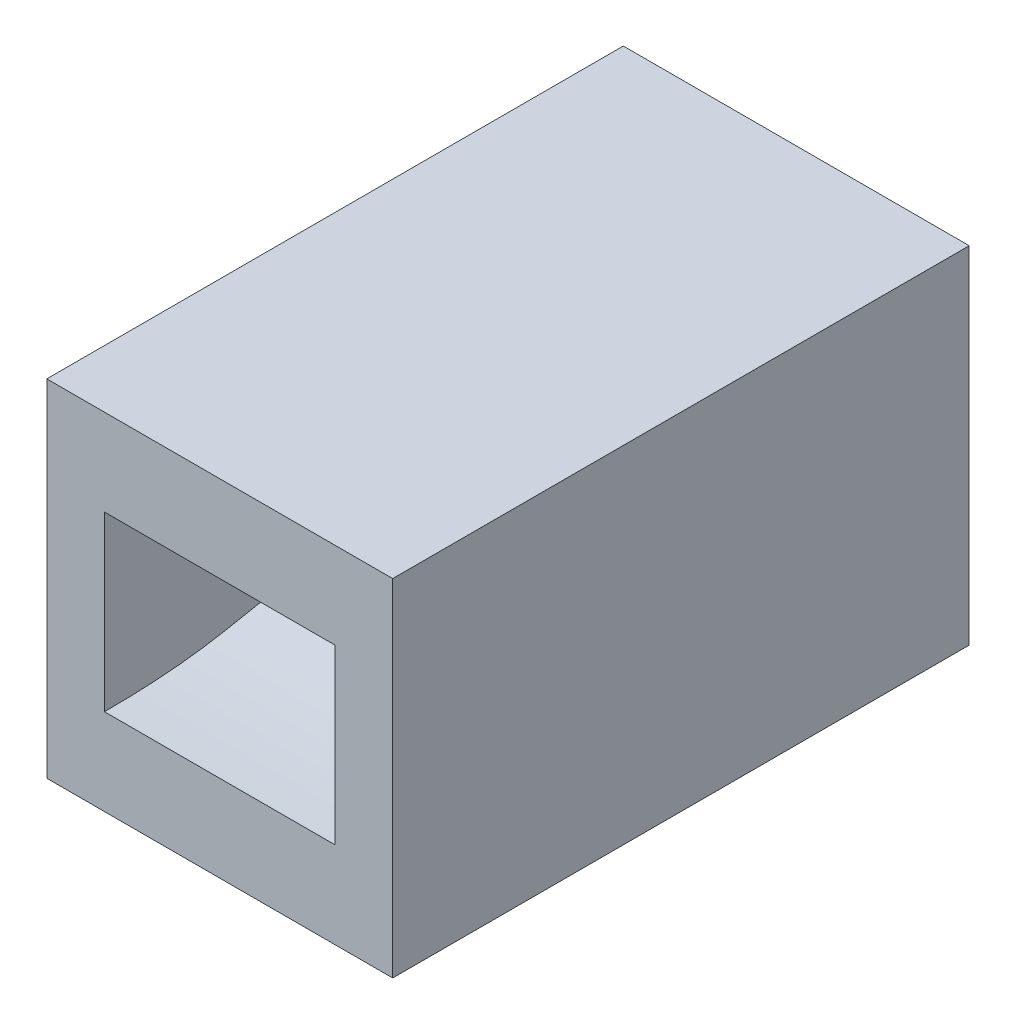
SolidWorks part; units mm, degrees
material "Custom Plastic"
ref_plane "Front Plane" through (0, 0, 0) normal (0, 0, 1) x (1, 0, 0)
ref_plane "Top Plane" through (0, 0, 0) normal (0, 1, 0) x (1, 0, 0)
ref_plane "Right Plane" through (0, 0, 0) normal (1, 0, 0) x (0, 0, -1)
other "Configuration Table"
sketch "Sketch1" plane through (0, 0, 0) normal (1, 0, 0) x (0, 0, -1)
  line L1 (0, 30) -> (-100, 30)
  line L2 (0, 30) -> (0, -30)
  line L3 (0, -30) -> (-100, -30)
  line L4 (-100, 30) -> (-100, -30)
  dimension "D1" = 60
  dimension "D2" = 100
extrude "Boss-Extrude1" add sketch "Sketch1" along normal mid plane 60
sketch "Sketch2" plane through (0, 0, 0) normal (1, 0, 0) x (0, 0, -1)
  line L0 (0, 15) -> (0, -15)
  line L1 (0, -30) -> (0, 30) construction
  line L2 (0, 15) -> (-25, 15) construction
  line L3 (-25, 15) -> (-25, 20) construction
  line L4 (-25, 20) -> (-50, 20) construction
  line L5 (0, -15) -> (-25, -15) construction
  line L6 (-25, -15) -> (-25, -10) construction
  line L7 (-25, -10) -> (-50, -10) construction
  line L8 (-50, 20) -> (-50, -10)
  line L9 (0, 0) -> (-100, 0) construction
  line L10 (-100, 30) -> (-100, -30) construction
  spline S0 degree 3 poles (0, 15) (-25, 15) (-25, 20) (-50, 20) knots 0 0 0 0 1 1 1 1
  spline S1 degree 3 poles (0, -15) (-25, -15) (-25, -10) (-50, -10) knots 0 0 0 0 1 1 1 1
  point P15 (-50, 0)
  point P16 (0, 0)
  point P17 (0, 0)
  point P18 (0, 11.4842)
  dimension "D1" = 30
  dimension "D2" = 5
extrude "Cut-Extrude1" cut sketch "Sketch2" against normal mid plane 40
mirror "Mirror1" about plane through (-20, 20, 50) normal (0, 0, 1) of "Cut-Extrude1"
